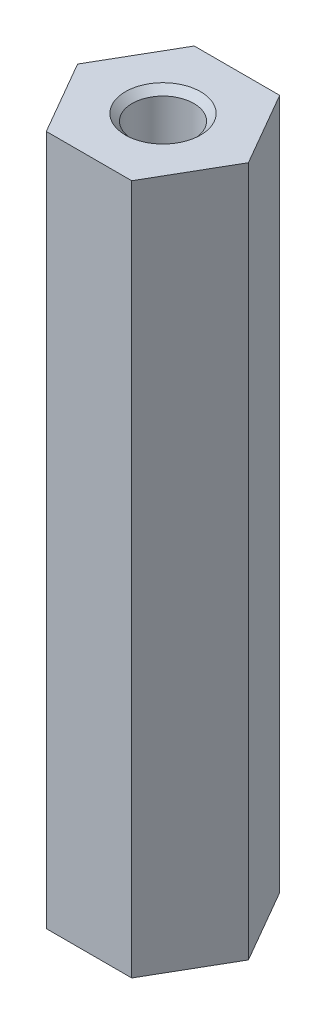
SolidWorks part; units mm, degrees
ref_plane "Ebene vorne" through (0, 0, 0) normal (0, 0, 1) x (1, 0, 0)
ref_plane "Ebene oben" through (0, 0, 0) normal (0, 1, 0) x (1, 0, 0)
ref_plane "Ebene rechts" through (0, 0, 0) normal (1, 0, 0) x (0, 0, -1)
sketch "Skizze1" plane through (0, 0, 0) normal (0, 1, 0) x (1, 0, 0)
  line L1 (3.4641, 0) -> (1.7321, 3)
  line L2 (1.7321, 3) -> (-1.7321, 3)
  line L3 (-1.7321, 3) -> (-3.4641, 0)
  line L4 (-3.4641, 0) -> (-1.7321, -3)
  line L5 (-1.7321, -3) -> (1.7321, -3)
  line L6 (1.7321, -3) -> (3.4641, 0)
  circle A0 centre (0, 0) radius 3 construction
  dimension "D1" = 6
extrude "Aufsatz-Linear austragen1" add sketch "Skizze1" along normal blind 28
hole_wizard "M3 Gewindebohrung1" positions "Skizze2" profile "Skizze3" tap size "M3" standard "DIN" end condition through all
sketch "Skizze2" plane through (0, 28, 0) normal (0, 1, 0) x (1, 0, 0)
  point P0 (0, 0)
cosmetic thread "Bohrungsgewinde1" parameters "D2"=3
sketch "Skizze3" plane through (0, 28, 0) normal (1, 0, 0) x (0, 0, 1)
  line L0 (0, 0) -> (0, 28)
  line L1 (0, 28) -> (1.25, 28)
  line L2 (1.25, 28) -> (1.25, 0.275)
  line L3 (1.25, 0.275) -> (1.525, 0)
  line L5 (1.525, 0) -> (0, 0)
  line L6 (-1.25, 0.275) -> (-1.525, 0) construction
  line L11 (0, -6.35) -> (0, 107.95) construction
  dimension "Bohrerdurchmesser" = 2.5
  dimension "Bohrungstiefe" = 28
  dimension "Senkdurchmesser (Oben)" = 3.05
  dimension "Senkwinkel (Oben)" = 90
